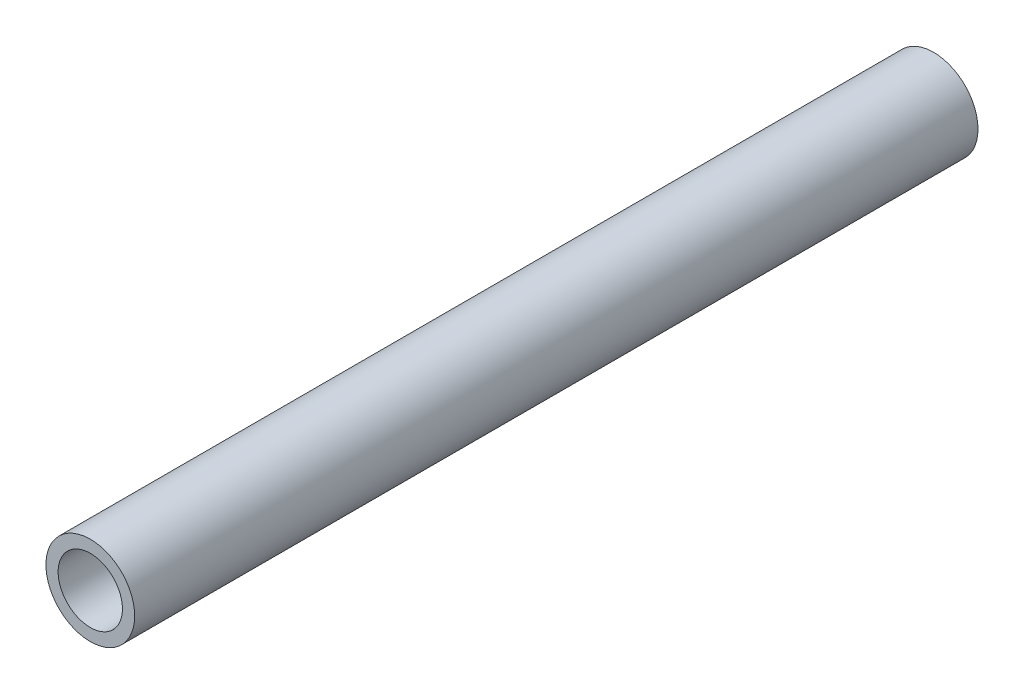
SolidWorks part; units mm, degrees
ref_plane "Front Plane" through (0, 0, 0) normal (0, 0, 1) x (1, 0, 0)
ref_plane "Top Plane" through (0, 0, 0) normal (0, 1, 0) x (1, 0, 0)
ref_plane "Right Plane" through (0, 0, 0) normal (1, 0, 0) x (0, 0, -1)
sketch "Sketch1" plane through (0, 0, 0) normal (0, 0, 1) x (1, 0, 0)
  circle A0 centre (0, 0) radius 10.6934
  circle A1 centre (0, 0) radius 7.747
  dimension "D1" = 21.3868
  dimension "D2" = 15.494
extrude "Boss-Extrude1" add sketch "Sketch1" along normal blind 203.2
